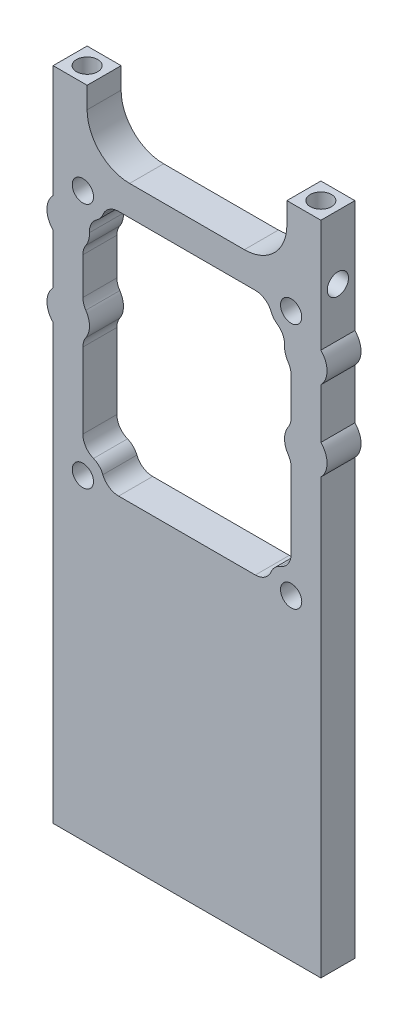
SolidWorks part; units mm, degrees
material "ABS"
ref_plane "Спереди" through (0, 0, 0) normal (0, 0, 1) x (1, 0, 0)
ref_plane "Сверху" through (0, 0, 0) normal (0, 1, 0) x (1, 0, 0)
ref_plane "Справа" through (0, 0, 0) normal (1, 0, 0) x (0, 0, -1)
sketch "Эскиз1" plane through (0, 0, 0) normal (0, 0, 1) x (1, 0, 0)
  line L0 (-23.5, 77.2034) -> (-23.5, 62.2034)
  line L1 (-31.5, -77.2034) -> (31.5, -77.2034)
  line L2 (-31.5, -77.2034) -> (-31.5, 77.2034)
  line L3 (-31.5, 77.2034) -> (31.5, 77.2034)
  line L4 (31.5, -77.2034) -> (31.5, 77.2034)
  line L5 (-31.5, -77.2034) -> (31.5, 77.2034) construction
  line L6 (-31.5, 77.2034) -> (31.5, -77.2034) construction
  line L7 (-23.5, 62.2034) -> (23.5, 62.2034)
  line L8 (23.5, 62.2034) -> (23.5, 77.2034)
  line L9 (-27.5, 77.2034) -> (-27.5, 37.5115) construction
  line L10 (0, 77.2034) -> (0, 0) construction
  line L11 (27.5, 77.2034) -> (27.5, 37.5115) construction
  point P0 (0, 0)
  dimension "D1" = 8
  dimension "D2" = 8
  dimension "D3" = 4
  dimension "D4" = 55
  dimension "D5" = 15
extrude "Бобышка-Вытянуть1" add sketch "Эскиз1" along normal blind 8 contours L8 L7 L0 L3 L2 L1 L4
sketch "Эскиз2" plane through (0, 77.2034, 0) normal (0, 1, 0) x (1, 0, 0)
  line L0 (-23.5, 0) -> (-31.5, -8) construction
  line L1 (0, 0) -> (0, -8) construction
  line L2 (-23.5, -8) -> (23.5, -8) construction
  circle A0 centre (-27.5, -4) radius 2.5
  circle A1 centre (27.5, -4) radius 2.5
  dimension "D1" = 5
extrude "Вырез-Вытянуть1" cut sketch "Эскиз2" against normal blind 6
sketch "Эскиз3" plane through (0, 0, 8) normal (0, 0, 1) x (1, 0, 0)
  line L0 (0, 62.2034) -> (0, -77.2034) construction
  line L1 (-23.5, 62.2034) -> (23.5, 62.2034) construction
  line L2 (-31.5, -77.2034) -> (31.5, -77.2034) construction
  line L4 (-24.5, -2.7966) -> (24.5, -2.7966) construction
  line L5 (-24.5, -2.7966) -> (-24.5, 55.2034) construction
  line L6 (-24.5, 55.2034) -> (24.5, 55.2034) construction
  line L7 (24.5, -2.7966) -> (24.5, 55.2034) construction
  line L8 (-24.5, -2.7966) -> (24.5, 55.2034) construction
  line L9 (-24.5, 55.2034) -> (24.5, -2.7966) construction
  circle A0 centre (-24.5, 55.2034) radius 2.5
  circle A1 centre (24.5, 55.2034) radius 2.5
  circle A2 centre (24.5, -2.7966) radius 2.5
  circle A3 centre (-24.5, -2.7966) radius 2.5
  point P6 (0, 0)
  point P16 (0, 26.2034)
  dimension "D3" = 5
  dimension "D1" = 49
  dimension "D2" = 7
  dimension "D4" = 58
extrude "Вырез-Вытянуть2" cut sketch "Эскиз3" against normal blind 6
fillet "Скругление1" radius 10 2 edges at (23.5, 62.2034, 4) (-23.5, 62.2034, 4)
sketch "Эскиз4" plane through (0, 0, 8) normal (0, 0, 1) x (1, 0, 0)
  line L0 (24.5, 55.2034) -> (-24.5, -2.7966) construction
  line L1 (31.5, -77.2034) -> (31.5, 77.2034) construction
  line L2 (-24.5, 50.2034) -> (24.5, 50.2034)
  line L3 (-24.5, 50.2034) -> (-24.5, 2.2034)
  line L4 (-24.5, 2.2034) -> (24.5, 2.2034)
  line L5 (24.5, 50.2034) -> (24.5, 2.2034)
  line L6 (-24.5, 50.2034) -> (24.5, 2.2034) construction
  line L7 (-24.5, 2.2034) -> (24.5, 50.2034) construction
  line L8 (-13.5, 62.2034) -> (13.5, 62.2034) construction
  line L9 (-19.5, -2.7966) -> (19.5, -2.7966)
  line L10 (-19.5, -2.7966) -> (-19.5, 55.2034)
  line L11 (-19.5, 55.2034) -> (19.5, 55.2034)
  line L12 (19.5, -2.7966) -> (19.5, 55.2034)
  line L13 (-19.5, -2.7966) -> (19.5, 55.2034) construction
  line L14 (-19.5, 55.2034) -> (19.5, -2.7966) construction
  point P4 (0, 26.2034)
  point P11 (0, 26.2034)
  dimension "D1" = 7
  dimension "D2" = 5
  dimension "D3" = 5
  dimension "D4" = 7
extrude "Вырез-Вытянуть3" cut sketch "Эскиз4" against normal blind 21 contours L4 L12 L2 L10 | L4 L10 L2 L3 | L2 L12 L11 L10 | L12 L4 L5 L2 | L9 L12 L4 L10
sketch "Эскиз5" plane through (0, 0, 0) normal (0, 0, -1) x (-1, 0, 0)
  line L0 (0, 62.2034) -> (0, -77.2034) construction
  line L1 (13.5, 62.2034) -> (-13.5, 62.2034) construction
  line L2 (31.5, -77.2034) -> (-31.5, -77.2034) construction
  line L4 (-27.95, 47.2034) -> (27.95, 47.2034) construction
  line L5 (-27.95, 47.2034) -> (-27.95, 28.4034) construction
  line L6 (-27.95, 28.4034) -> (27.95, 28.4034) construction
  line L7 (27.95, 47.2034) -> (27.95, 28.4034) construction
  line L8 (-27.95, 47.2034) -> (27.95, 28.4034) construction
  line L9 (-27.95, 28.4034) -> (27.95, 47.2034) construction
  circle A0 centre (-27.95, 47.2034) radius 5
  circle A1 centre (-27.95, 28.4034) radius 5
  circle A2 centre (27.95, 28.4034) radius 5
  circle A3 centre (27.95, 47.2034) radius 5
  point P6 (0, 37.8034)
  dimension "D4" = 10
  dimension "D1" = 18.8
  dimension "D2" = 55.9
  dimension "D3" = 15
extrude "Бобышка-Вытянуть2" add sketch "Эскиз5" against normal up to surface (8 mm away) up to face at (0, 26.2034, 8)
fillet "Скругление2" radius 4 4 edges at (-19.5, 2.2034, 4) (19.5, 2.2034, 4) (19.5, 50.2034, 4) (-19.5, 50.2034, 4)
fillet "Скругление3" radius 4 14 edges at (-24.5, 32.0224, 4) (-24.5, 24.7843, 4) (-24.5, 43.5843, 4) (-23.95, 50.2034, 4) (-19.5, 55.2034, 4) (24.5, 32.0224, 4) (24.5, 24.7843, 4) (24.5, 43.5843, 4) (19.5, 55.2034, 4) (23.95, 50.2034, 4) (24.5, 2.2034, 4) (19.5, -2.7966, 4) (-19.5, -2.7966, 4) (-24.5, 2.2034, 4)
sketch "Эскиз6" plane through (0, 0, 0) normal (0, 0, -1) x (-1, 0, 0)
  circle A0 centre (-27.95, 47.2034) radius 2.5
  circle A1 centre (27.95, 47.2034) radius 2.5
  circle A2 centre (27.95, 28.4034) radius 2.5
  circle A3 centre (-27.95, 28.4034) radius 2.5
  dimension "D1" = 5
extrude "Вырез-Вытянуть4" cut sketch "Эскиз6" against normal blind 6
sketch "Эскиз7" plane through (-31.5, 0, 0) normal (-1, 0, 0) x (0, 0, 1)
  line L0 (4, 77.2034) -> (4, 51.4454) construction
  line L1 (4, 71.2034) -> (4, 77.2034) construction
  line L3 (8, 77.2034) -> (0, 77.2034) construction
  circle A0 centre (4, 62.2034) radius 2.5
  dimension "D1" = 5
  dimension "D2" = 15
extrude "Вырез-Вытянуть5" cut sketch "Эскиз7" against normal blind 6
mirror "Зеркальное отражение1" about plane through (0, 0, 0) normal (1, 0, 0) of "Вырез-Вытянуть5"
